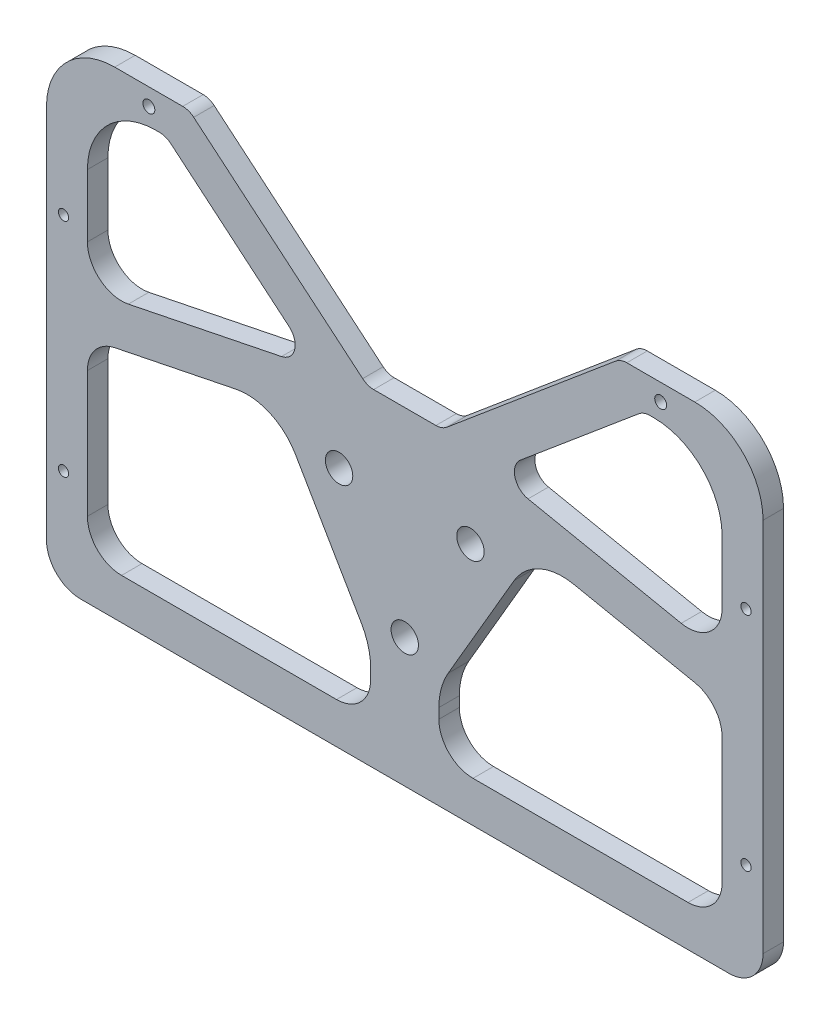
SolidWorks part; units mm, degrees
ref_plane "前基準面" through (0, 0, 0) normal (0, 0, 1) x (1, 0, 0)
ref_plane "上基準面" through (0, 0, 0) normal (0, 1, 0) x (1, 0, 0)
ref_plane "右基準面" through (0, 0, 0) normal (1, 0, 0) x (0, 0, -1)
sketch "Sketch1" plane through (0, 0, 0) normal (0, 0, 1) x (1, 0, 0)
  line L0 (0, 83.5398) -> (0, -125.3098) construction
  line L2 (-95, -60) -> (95, -60)
  line L3 (-105, -50) -> (-105, 60)
  line L5 (105, -50) -> (105, 60)
  line L6 (-105, -60) -> (105, 60) construction
  line L7 (-105, 60) -> (105, -60) construction
  line L8 (93, -1.0046) -> (93, -38)
  line L9 (-83, -48) -> (-20, -48)
  line L10 (-93, -38) -> (-93, -1.0046)
  line L11 (-93, 48) -> (93, 48) construction
  line L12 (93, -48) -> (93, 48) construction
  line L13 (-93, -48) -> (93, -48) construction
  line L14 (-93, -48) -> (-93, 48) construction
  line L15 (-105, 60) -> (105, 60) construction
  line L16 (-105, -60) -> (-105, 60) construction
  line L17 (-105, -60) -> (105, -60) construction
  line L18 (105, -60) -> (105, 60) construction
  line L19 (0, 0) -> (-61.5237, 35.5207) construction
  line L20 (84.9937, 8.7946) -> (49.4486, 16.0264)
  line L21 (-93, 31.651) -> (-93, 50)
  line L22 (-66.8269, 30) -> (70.1999, 30) construction
  line L23 (-84.9937, 8.7946) -> (-49.4486, 16.0264)
  line L24 (-32.0562, 8.2322) -> (-12.7184, -24.9642)
  line L25 (32.0562, 8.2322) -> (12.7184, -24.9642)
  line L26 (20, -48) -> (83, -48)
  line L27 (93, 31.651) -> (93, 50)
  line L28 (-10, -38) -> (-10, -35.0313)
  line L29 (-100, 73.1057) -> (-100, -98.0123) construction
  line L30 (10, -38) -> (10, -35.0313)
  line L31 (100, 71.0716) -> (100, -107.1657) construction
  line L32 (-81.0063, 21.8517) -> (-42.9297, 29.5985)
  line L33 (81.0063, 21.8517) -> (42.9297, 29.5985)
  line L34 (-38.9423, 30) -> (38.9423, 30)
  line L35 (-85, 80) -> (85, 80)
  line L37 (-73, 70) -> (73, 70)
  arc A0 (-105, 60) -> (-85, 80) centre (-85, 60) cw
  arc A1 (93, -38) -> (83, -48) centre (83, -38) cw
  arc A2 (-83, -48) -> (-93, -38) centre (-83, -38) cw
  arc A5 (-105, -50) -> (-95, -60) centre (-95, -50) ccw
  arc A6 (95, -60) -> (105, -50) centre (95, -50) ccw
  arc A7 (105, 60) -> (85, 80) centre (85, 60) ccw
  arc A12 (-12.7184, -24.9642) -> (-10, -35.0313) centre (-30, -35.0313) cw
  arc A13 (12.7184, -24.9642) -> (10, -35.0313) centre (30, -35.0313) ccw
  arc A14 (32.0562, 8.2322) -> (49.4486, 16.0264) centre (46.188, 0) cw
  arc A15 (-32.0562, 8.2322) -> (-49.4486, 16.0264) centre (-46.188, 0) ccw
  arc A17 (38.9423, 30) -> (42.9297, 29.5985) centre (38.9423, 10) cw
  arc A18 (-42.9297, 29.5985) -> (-38.9423, 30) centre (-38.9423, 10) cw
  arc A19 (20, -48) -> (10, -38) centre (20, -38) cw
  arc A20 (-20, -48) -> (-10, -38) centre (-20, -38) ccw
  arc A21 (-93, -1.0046) -> (-84.9937, 8.7946) centre (-83, -1.0046) cw
  arc A22 (93, -1.0046) -> (84.9937, 8.7946) centre (83, -1.0046) ccw
  arc A23 (93, 31.651) -> (81.0063, 21.8517) centre (83, 31.651) cw
  arc A24 (-93, 31.651) -> (-81.0063, 21.8517) centre (-83, 31.651) ccw
  arc A25 (93, 50) -> (73, 70) centre (73, 50) ccw
  arc A26 (-73, 70) -> (-93, 50) centre (-73, 50) ccw
  spline S1 degree 3 poles (-85.7038, 19.8656) (-85.7188, 19.8643) (-85.8694, 19.8508) (-86.1654, 19.8244) (-86.7586, 19.7722) (-87.5568, 19.705) (-88.5978, 19.6254) (-89.3837, 19.5729) (-90.1557, 19.5266) (-90.9081, 19.4857) (-91.7011, 19.452) (-92.5653, 19.4219) (-93.5061, 19.3971) (-94.6818, 19.3863) (-95.6597, 19.3925) (-96.4117, 19.4054) (-97.1825, 19.4275) (-97.8845, 19.4569) (-98.4218, 19.486) (-98.9655, 19.5197) (-99.61, 19.5665) (-100.317, 19.6301) (-100.8904, 19.6904) (-101.3238, 19.7407) (-101.76, 19.7964) (-102.1984, 19.8577) (-102.6385, 19.9251) (-102.9327, 19.9743) (-103.0799, 20) knots 0.184037 0.184037 0.184037 0.184037 0.1875 0.21875 0.25 0.3125 0.375 0.4375 0.444444 0.5 0.555556 0.5625 0.625 0.6875 0.71875 0.75 0.78125 0.8125 0.833333 0.84375 0.875 0.90625 0.921875 0.9375 0.953125 0.96875 0.984375 1 1 1 1 construction
  point P3 (0, 0)
  point P23 (-105, 80)
  point P40 (95, 22)
  point P47 (0, 0)
  point P50 (-34.641, 20)
  point P60 (-10, -29.6307)
  point P63 (10, -29.6307)
  point P66 (34.641, 20)
  point P69 (-34.641, 20)
  point P87 (40.9562, 30)
  point P90 (-40.9562, 30)
  point P100 (-93, 7.1657)
  point P103 (93, 7.1657)
  point P106 (93, 19.4116)
  point P109 (-93, 19.4116)
  dimension "D4" = 10
  dimension "D5" = 149.778
  dimension "D6" = 140
  dimension "D13" = 20
  dimension "D9" = 20
  dimension "D12" = 10
  dimension "D2" = 20
  dimension "D10" = 20
  dimension "D17" = 40
  dimension "D18" = 10
  dimension "D19" = 10
  dimension "D1" = 120
  dimension "D8" = 70
  dimension "D11" = 20
  dimension "D14" = 11.5
  dimension "D15" = 5
  dimension "D7" = 210
  dimension "D16" = 12
  dimension "D3" = 12
extrude "Boss-Extrude1" add sketch "Sketch1" along normal mid plane 6
sketch "Sketch2" plane through (0, 0, 3) normal (0, 0, 1) x (1, 0, 0)
  line L0 (100, 71.0716) -> (100, -107.1657) construction
  line L1 (-95, -60) -> (95, -60) construction
  line L4 (0, 83.5398) -> (0, -125.3098) construction
  circle A0 centre (100, 35) radius 1.5
  circle A1 centre (100, -30) radius 1.5
  circle A2 centre (-100, -30) radius 1.5
  circle A3 centre (-100, 35) radius 1.5
  dimension "D1" = 3
  dimension "D2" = 3
  dimension "D3" = 30
  dimension "D4" = 65
extrude "Cut-Extrude1" cut sketch "Sketch2" against normal through all both and the other way through all
sketch "Sketch3" plane through (0, 0, 3) normal (0, 0, 1) x (1, 0, 0)
  line L0 (0, 0) -> (-19.2474, 11.1125) construction
  line L1 (19.2474, 11.1125) -> (0, 0) construction
  line L2 (0, -22.225) -> (0, 0) construction
  circle A0 centre (0, 0) radius 22.225 construction
  dimension "D1" = 44.45
  dimension "D2" = 120
  dimension "D3" = 120
hole_wizard "O (0.316) Diameter Hole1" positions "Sketch4" profile "Sketch5" hole size "O" standard "ANSI Inch"
sketch "Sketch4" plane through (0, 0, 3) normal (0, 0, 1) x (1, 0, 0)
  point P0 (-19.2474, 11.1125)
  point P3 (19.2474, 11.1125)
  point P6 (0, -22.225)
sketch "Sketch5" plane through (-19.2474, 11.1125, 3) normal (1, 0, 0) x (0, -1, 0)
  line L0 (0, 0) -> (0, 12.4114)
  line L1 (0, 12.4114) -> (4.0132, 10)
  line L2 (4.0132, 10) -> (4.0132, 0)
  line L5 (4.0132, 0) -> (0, 0)
  line L10 (0, 12.4114) -> (-4.0132, 10) construction
  line L11 (0, -6.35) -> (0, 107.95) construction
  dimension "Hole Dia." = 8.0264
  dimension "Hole Depth" = 10
  dimension "Drill Angle" = 118
sketch "Sketch6" plane through (0, 0, 3) normal (0, 0, 1) x (1, 0, 0)
  line L0 (85, 80) -> (-85, 80) construction
  line L1 (-70, 80) -> (70, 80)
  line L2 (-70, 80) -> (-70, 70)
  line L3 (-70, 70) -> (70, 70)
  line L4 (70, 80) -> (70, 70)
  line L5 (73, 70) -> (-73, 70) construction
  circle A0 centre (0, 0) radius 22.225 construction
  dimension "D1" = 70
  dimension "D2" = 70
extrude "Cut-Extrude2" cut sketch "Sketch6" against normal blind 10
sketch "Sketch7" plane through (0, 0, 3) normal (0, 0, 1) x (1, 0, 0)
  circle A0 centre (-75, 75) radius 1.75
  circle A1 centre (75, 75) radius 1.75
  circle A2 centre (0, 0) radius 22.225 construction
  dimension "D1" = 3.5
  dimension "D2" = 3.5
  dimension "D3" = 75
  dimension "D4" = 75
  dimension "D5" = 75
extrude "Cut-Extrude3" cut sketch "Sketch7" against normal blind 10
sketch "Sketch8" plane through (0, 0, -3) normal (0, 0, -1) x (-1, 0, 0)
  line L0 (-70, 80) -> (-70, 70)
  line L1 (-70, 70) -> (-25.9648, 33.05)
  line L5 (69.8215, 80) -> (70, 80)
  line L6 (70, 80) -> (70, 70)
  line L7 (70, 70) -> (25.9648, 33.05)
  line L10 (-73, 70) -> (-70, 70) construction
  line L11 (70, 70) -> (73, 70) construction
  line L13 (-70, 80) -> (-63.2489, 80)
  line L14 (-63.2489, 80) -> (-10.9392, 36.107)
  line L15 (70, 80) -> (63.2489, 80)
  line L16 (63.2489, 80) -> (10.9392, 36.107)
  line L17 (-85, 80) -> (-70, 80) construction
  line L18 (10.9392, 36.107) -> (-10.9392, 36.107)
  line L21 (42.9297, 29.5985) -> (25.9648, 33.05)
  line L22 (-25.9648, 33.05) -> (-42.9297, 29.5985)
  line L24 (81.0063, 21.8517) -> (42.9297, 29.5985) construction
  line L27 (-42.9297, 29.5985) -> (-81.0063, 21.8517) construction
  line L28 (25.9648, 33.05) -> (10.9392, 36.107) construction
  line L29 (-10.9392, 36.107) -> (-25.9648, 33.05) construction
  line L30 (42.9297, 29.5985) -> (-42.9297, 29.5985)
  dimension "D1" = 140
  dimension "D2" = 140
  dimension "D3" = 12
  dimension "D4" = 12
extrude "Boss-Extrude3" add sketch "Sketch8" against normal blind 6
fillet "Fillet2" radius 5 8 edges at (-70, 70, 0) (70, 70, 0) (-63.2489, 80, 0) (63.2489, 80, 0) (10.9392, 36.107, 0) (-10.9392, 36.107, 0) (-25.9648, 33.05, 0) (25.9648, 33.05, 0)
